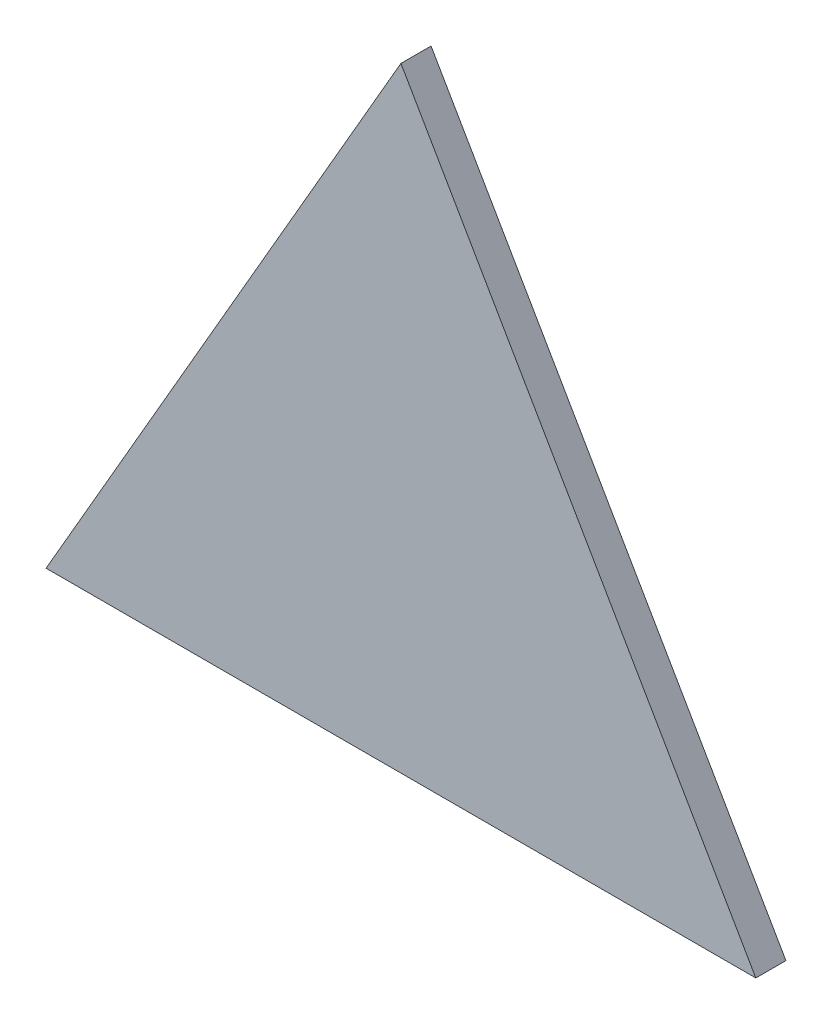
SolidWorks part; units mm, degrees
ref_plane "前视基准面" through (0, 0, 0) normal (0, 0, 1) x (1, 0, 0)
ref_plane "上视基准面" through (0, 0, 0) normal (0, 1, 0) x (1, 0, 0)
ref_plane "右视基准面" through (0, 0, 0) normal (1, 0, 0) x (0, 0, -1)
sketch "草图1" plane through (0, 0, 0) normal (0, 0, 1) x (1, 0, 0)
  line L0 (-11.785, 0) -> (11.785, 0)
  line L5 (-11.785, 0) -> (0, 20.4122)
  line L6 (0, 20.4122) -> (11.785, 0)
  point P2 (0, 0)
  dimension "D1" = 23.57
  dimension "D2" = 60
  dimension "D3" = 60
extrude "凸台-拉伸1" add sketch "草图1" along normal blind 1
